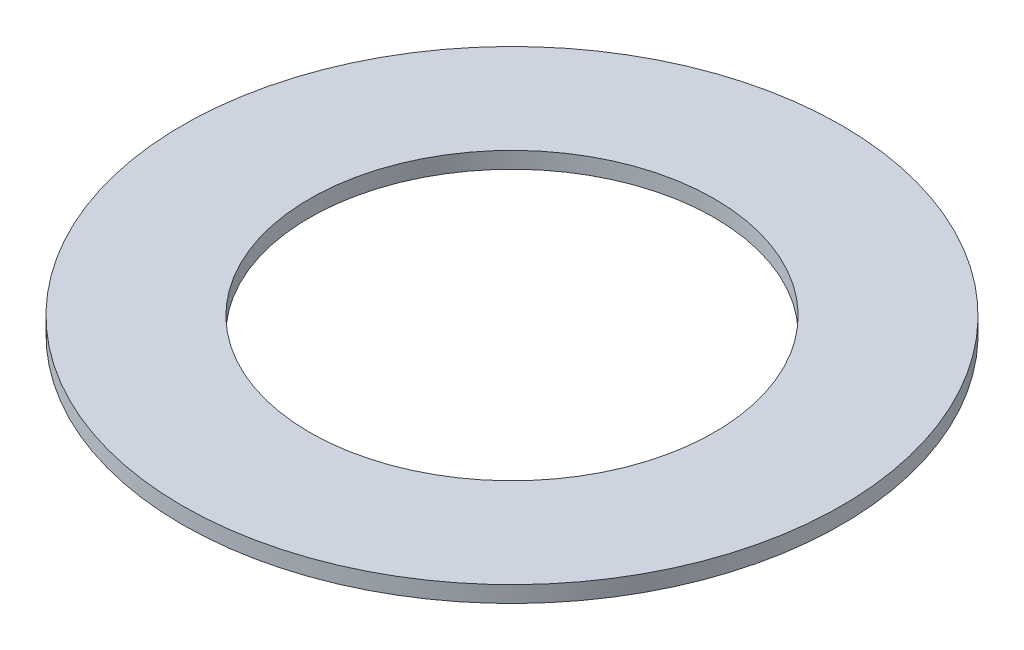
SolidWorks part; units mm, degrees
ref_plane "Front Plane" through (0, 0, 0) normal (0, 0, 1) x (1, 0, 0)
ref_plane "Top Plane" through (0, 0, 0) normal (0, 1, 0) x (1, 0, 0)
ref_plane "Right Plane" through (0, 0, 0) normal (1, 0, 0) x (0, 0, -1)
sketch "Sketch1" plane through (0, 0, 0) normal (0, 1, 0) x (1, 0, 0)
  circle A0 centre (0, 0) radius 80.7
  circle A1 centre (0, 0) radius 49.55
  dimension "D1" = 161.4
  dimension "D2" = 99.1
extrude "Boss-Extrude1" add sketch "Sketch1" along normal blind 4
